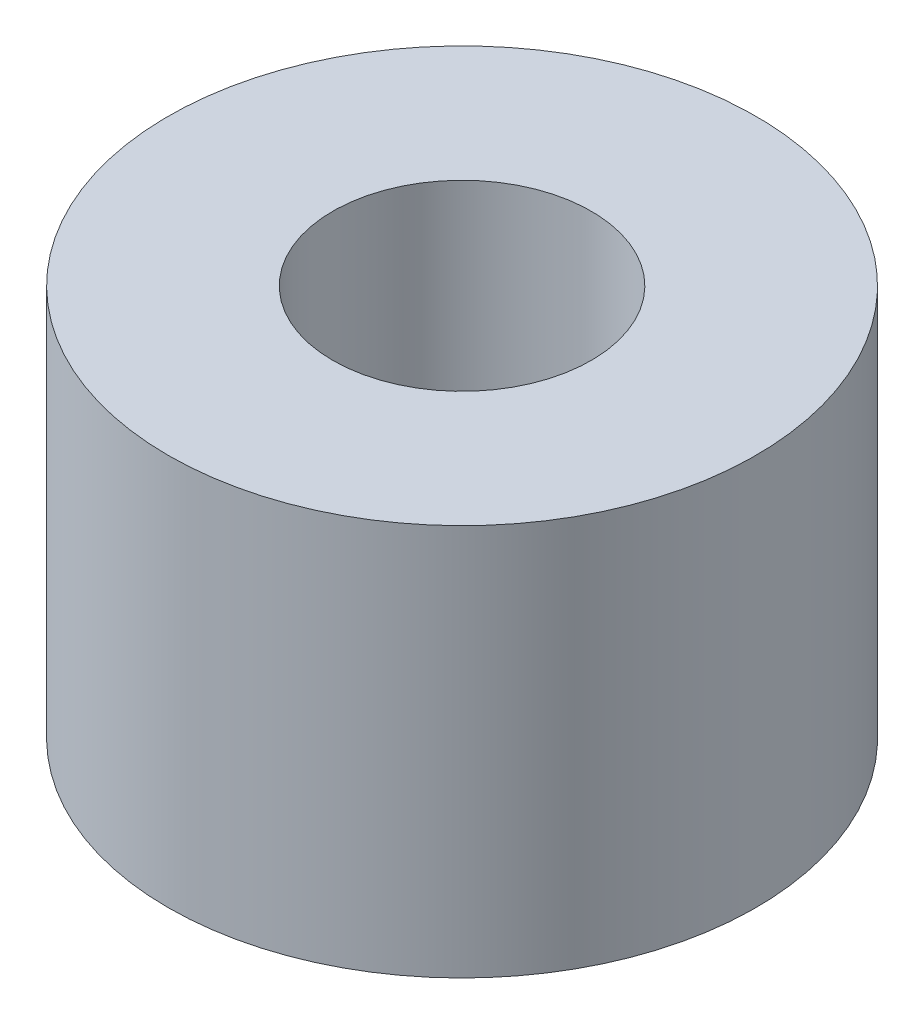
SolidWorks part; units mm, degrees
material "Алюминиевая бронза"
ref_plane "Спереди" through (0, 0, 0) normal (0, 0, 1) x (1, 0, 0)
ref_plane "Сверху" through (0, 0, 0) normal (0, 1, 0) x (1, 0, 0)
ref_plane "Справа" through (0, 0, 0) normal (1, 0, 0) x (0, 0, -1)
sketch "Эскиз1" plane through (0, 0, 0) normal (0, 1, 0) x (1, 0, 0)
  circle A0 centre (0, 0) radius 3
  circle A1 centre (0, 0) radius 1.32
extrude "Бобышка-Вытянуть1" add sketch "Эскиз1" along normal blind 4
